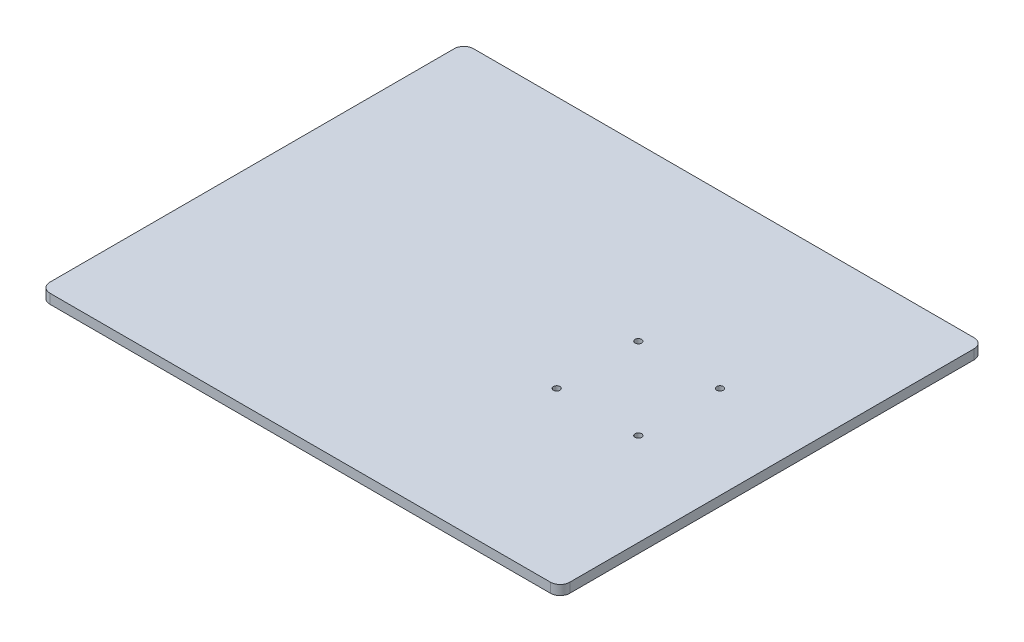
SolidWorks part; units mm, degrees
material "AISI 304"
ref_plane "前视基准面" through (0, 0, 0) normal (0, 0, 1) x (1, 0, 0)
ref_plane "上视基准面" through (0, 0, 0) normal (0, 1, 0) x (1, 0, 0)
ref_plane "右视基准面" through (0, 0, 0) normal (1, 0, 0) x (0, 0, -1)
sketch "Sketch1" plane through (0, 0, 0) normal (0, 1, 0) x (1, 0, 0)
  line L1 (260, -220) -> (-260, -220)
  line L2 (270, -210) -> (270, 210)
  line L3 (260, 220) -> (-260, 220)
  line L4 (-270, -210) -> (-270, 210)
  line L5 (270, -220) -> (-270, 220) construction
  line L6 (270, 220) -> (-270, -220) construction
  arc A0 (-260, -220) -> (-270, -210) centre (-260, -210) cw
  arc A1 (-260, 220) -> (-270, 210) centre (-260, 210) ccw
  arc A2 (270, 210) -> (260, 220) centre (260, 210) ccw
  arc A3 (260, -220) -> (270, -210) centre (260, -210) ccw
  point P0 (0, 0)
  dimension "D3" = 10
  dimension "D1" = 540
  dimension "D2" = 440
extrude "Extrude1" add sketch "Sketch1" along normal blind 10
sketch "Sketch2" plane through (0, 10, 0) normal (0, 1, 0) x (1, 0, 0)
  line L0 (270, 0) -> (-270, 0) construction
  line L1 (270, -210) -> (270, 210) construction
  line L2 (-270, 210) -> (-270, -210) construction
  line L4 (88.8158, 42.4264) -> (173.6686, 42.4264) construction
  line L5 (88.8158, 42.4264) -> (88.8158, -42.4264) construction
  line L6 (88.8158, -42.4264) -> (173.6686, -42.4264) construction
  line L7 (173.6686, 42.4264) -> (173.6686, -42.4264) construction
  line L8 (88.8158, 42.4264) -> (173.6686, -42.4264) construction
  line L9 (88.8158, -42.4264) -> (173.6686, 42.4264) construction
  circle A0 centre (131.2422, 0) radius 60 construction
  dimension "D1" = 120
hole_wizard "M8 Tapped Hole1" positions "3DSketch1" profile "Sketch3" tap size "M8" standard "GB"
sketch3d "3DSketch1"
  point P0 (88.8158, 10, -42.4264)
  point P3 (88.8158, 10, 42.4264)
  point P6 (173.6686, 10, 42.4264)
  point P9 (173.6686, 10, -42.4264)
sketch "Sketch3" plane through (88.8158, 10, -42.4264) normal (1, 0, 0) x (0, 0, 1)
  line L0 (0, 0) -> (0, 21.7929)
  line L1 (0, 21.7929) -> (3.4, 19.75)
  line L2 (3.4, 19.75) -> (3.4, 0)
  line L5 (3.4, 0) -> (0, 0)
  line L10 (0, 21.7929) -> (-3.4, 19.75) construction
  line L11 (0, -6.35) -> (0, 107.95) construction
  dimension "螺纹孔钻头直径" = 6.8
  dimension "螺纹孔钻头深度" = 19.75
  dimension "导头角度" = 118
cosmetic thread "Cosmetic Thread1" parameters "D1"=10, "D2"=8
cosmetic thread "Cosmetic Thread2" parameters "D1"=10, "D2"=8
cosmetic thread "Cosmetic Thread3" parameters "D1"=10, "D2"=8
cosmetic thread "Cosmetic Thread4" parameters "D1"=10, "D2"=8
